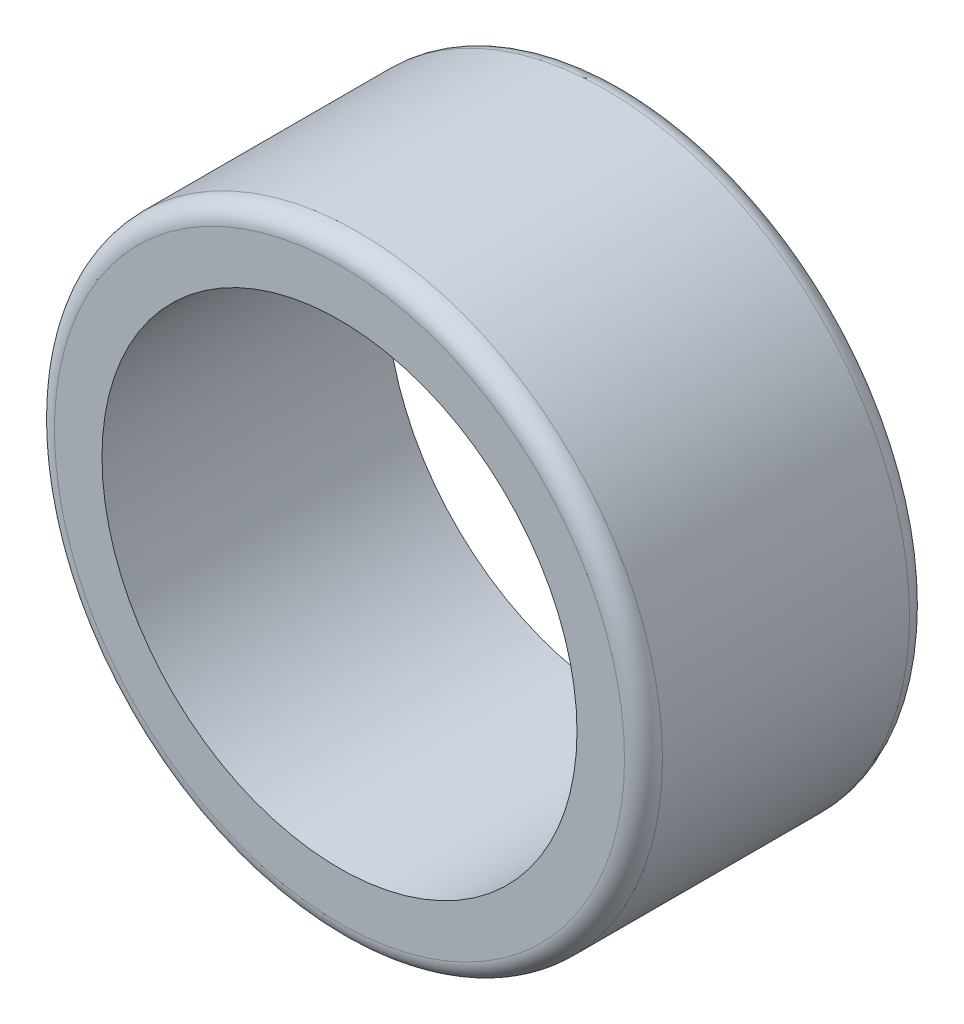
SolidWorks part; units mm, degrees
material "BUTYL"
ref_plane "Plan1" through (0, 0, 0) normal (0, 0, 1) x (1, 0, 0)
ref_plane "Plan2" through (0, 0, 0) normal (0, 1, 0) x (1, 0, 0)
ref_plane "Plan3" through (0, 0, 0) normal (1, 0, 0) x (0, 0, -1)
sketch "Esquisse1" plane through (0, 0, 0) normal (0, 0, 1) x (1, 0, 0)
  circle A0 centre (0, 0) radius 25
  circle A1 centre (0, 0) radius 32
  dimension "D1" = 50
  dimension "D2" = 64
extrude "Base-Extrusion" add sketch "Esquisse1" along normal blind 30
fillet "Congé1" radius 2
